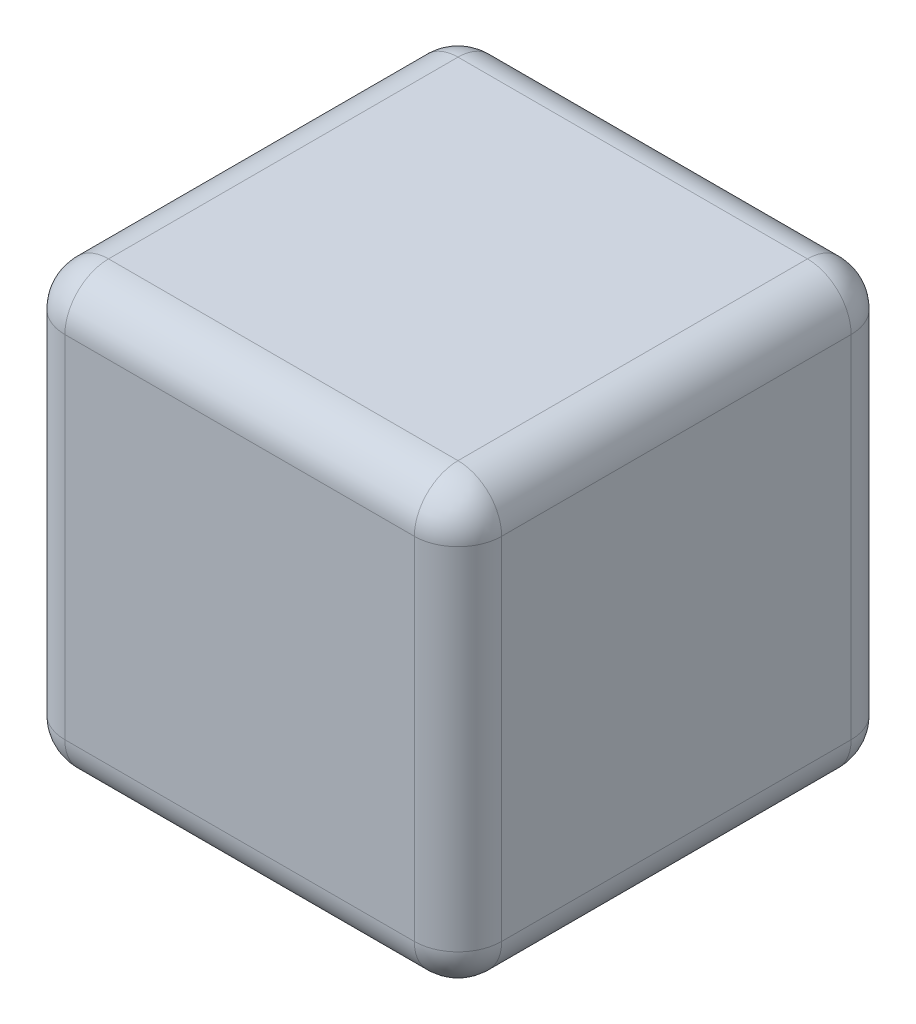
SolidWorks part; units mm, degrees
ref_plane "Front Plane" through (0, 0, 0) normal (0, 0, 1) x (1, 0, 0)
ref_plane "Top Plane" through (0, 0, 0) normal (0, 1, 0) x (1, 0, 0)
ref_plane "Right Plane" through (0, 0, 0) normal (1, 0, 0) x (0, 0, -1)
sketch "Sketch1" plane through (0, 0, 0) normal (0, 1, 0) x (1, 0, 0)
  line L1 (0, 0) -> (-20, 0)
  line L2 (0, 0) -> (0, 20)
  line L3 (0, 20) -> (-20, 20)
  line L4 (-20, 0) -> (-20, 20)
  point P4 (0, 0)
  point P5 (0, 0)
  point P6 (0, 0)
  point P7 (0, 0)
  point P8 (0, 0)
  point P11 (0, 0)
  point P12 (0, 0)
  dimension "D1" = 20
  dimension "D2" = 20
extrude "Boss-Extrude1" add sketch "Sketch1" along normal blind 20.066 contours L4 L3 L2 L1
fillet "Fillet1" radius 2 12 edges at (0, 10.033, 0) (0, 20.066, -10) (0, 10.033, -20) (0, 0, -10) (-20, 10.033, -20) (-20, 10.033, 0) (-10, 0, -20) (-20, 0, -10) (-10, 0, 0) (-20, 20.066, -10) (-10, 20.066, -20) (-10, 20.066, 0)
